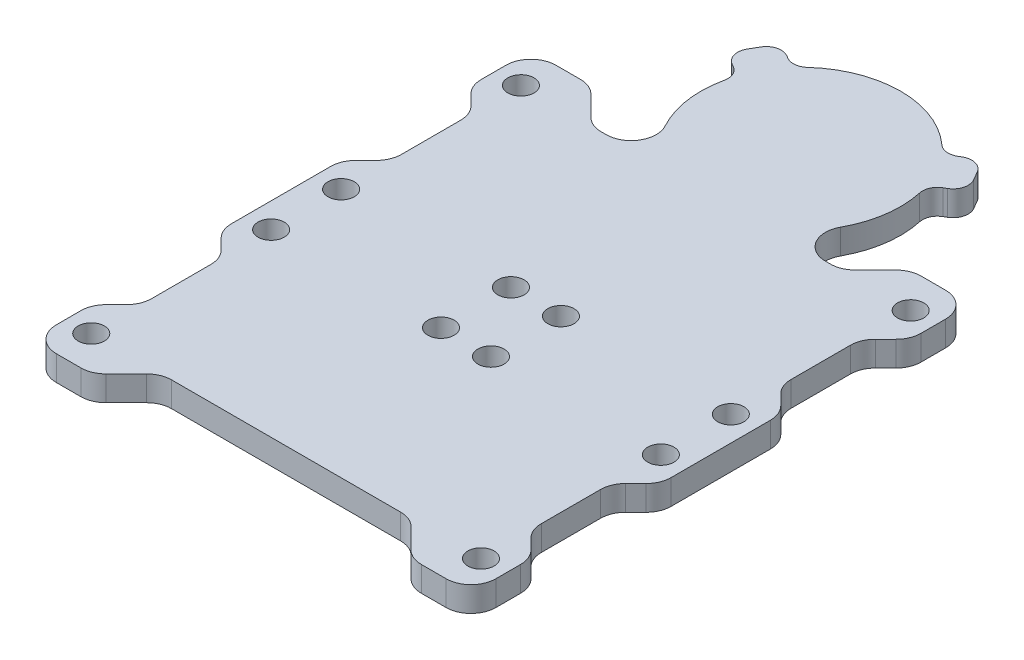
SolidWorks part; units mm, degrees
ref_plane "Front Plane" through (0, 0, 0) normal (0, 0, 1) x (1, 0, 0)
ref_plane "Top Plane" through (0, 0, 0) normal (0, 1, 0) x (1, 0, 0)
ref_plane "Right Plane" through (0, 0, 0) normal (1, 0, 0) x (0, 0, -1)
sketch "Sketch1" plane through (0, 0, 0) normal (0, 1, 0) x (1, 0, 0)
  line L0 (-42.5355, 36.5355) -> (-40.4645, 34.4645)
  line L1 (-39, 50) -> (-34.0711, 50)
  line L2 (-44, 45) -> (-44, 40.0711)
  line L3 (-39, -50) -> (-34.0711, -50)
  line L4 (44, 45) -> (44, 40.0711)
  line L5 (-39, 30.9289) -> (-39, 19.0711)
  line L6 (-40.4645, 15.5355) -> (-42.5355, 13.4645)
  line L7 (-44, 9.9289) -> (-44, -9.9289)
  line L8 (-42.5355, -13.4645) -> (-40.4645, -15.5355)
  line L9 (-39, -19.0711) -> (-39, -30.9289)
  line L10 (-40.4645, -34.4645) -> (-42.5355, -36.5355)
  line L11 (-44, -40.0711) -> (-44, -45)
  line L12 (-44, 12) -> (-44, -12)
  line L13 (-44, -40.0711) -> (-44, -50)
  line L14 (0, -55) -> (0, 55) construction
  line L15 (44, -40.0711) -> (44, -45)
  line L16 (44, 12) -> (44, -12)
  line L17 (44, -40.0711) -> (44, -45)
  line L18 (40.4645, -34.4645) -> (42.5355, -36.5355)
  line L19 (39, -19.0711) -> (39, -30.9289)
  line L20 (42.5355, -13.4645) -> (40.4645, -15.5355)
  line L21 (44, 9.9289) -> (44, -9.9289)
  line L22 (40.4645, 15.5355) -> (42.5355, 13.4645)
  line L23 (39, 30.9289) -> (39, 19.0711)
  line L24 (44, 45) -> (44, 40.0711)
  line L25 (42.5355, 36.5355) -> (40.4645, 34.4645)
  line L26 (44, -40.0711) -> (44, -45)
  line L27 (44, 12) -> (44, -12)
  line L28 (-30.5355, -48.5355) -> (-26.4645, -44.4645)
  line L29 (-22.9289, -43) -> (22.9289, -43)
  line L30 (26.4645, -44.4645) -> (30.5355, -48.5355)
  line L31 (34.0711, -50) -> (39, -50)
  line L32 (-30.5355, 48.5355) -> (-26.4645, 44.4645)
  line L33 (-22.9289, 43) -> (-21.9317, 43)
  line L34 (30.5355, 48.5355) -> (26.4645, 44.4645)
  line L35 (22.9289, 43) -> (21.9317, 43)
  line L36 (0, 60) -> (-17.3205, 70) construction
  line L37 (34.0711, 50) -> (39, 50)
  line L42 (-20.9737, 67.4903) -> (-21.5686, 67.8339)
  line L43 (-22.6667, 71.9319) -> (-21.6667, 73.664)
  line L44 (-17.5686, 74.7621) -> (-16.9737, 74.4186)
  line L45 (0, 60) -> (17.3205, 70) construction
  line L46 (17.5686, 74.7621) -> (16.9737, 74.4186)
  line L47 (22.6667, 71.9319) -> (21.6667, 73.664)
  line L48 (20.9737, 67.4903) -> (21.5686, 67.8339)
  circle A0 centre (-39, 43) radius 2.625
  circle A5 centre (-39, 7) radius 2.625
  circle A6 centre (-39, -7) radius 2.625
  circle A7 centre (-39, -43) radius 2.625
  arc A8 (-39, 50) -> (-44, 45) centre (-39, 45) ccw
  arc A9 (-42.5355, 36.5355) -> (-44, 40.0711) centre (-39, 40.0711) cw
  arc A10 (-40.4645, 34.4645) -> (-39, 30.9289) centre (-44, 30.9289) cw
  arc A11 (-39, 19.0711) -> (-40.4645, 15.5355) centre (-44, 19.0711) cw
  arc A12 (-42.5355, 13.4645) -> (-44, 9.9289) centre (-39, 9.9289) ccw
  arc A13 (-44, -9.9289) -> (-42.5355, -13.4645) centre (-39, -9.9289) ccw
  arc A14 (-40.4645, -15.5355) -> (-39, -19.0711) centre (-44, -19.0711) cw
  arc A15 (-39, -30.9289) -> (-40.4645, -34.4645) centre (-44, -30.9289) cw
  arc A16 (-42.5355, -36.5355) -> (-44, -40.0711) centre (-39, -40.0711) ccw
  arc A17 (-44, -45) -> (-39, -50) centre (-39, -45) ccw
  arc A18 (44, -45) -> (39, -50) centre (39, -45) cw
  arc A19 (42.5355, -36.5355) -> (44, -40.0711) centre (39, -40.0711) cw
  arc A20 (39, -30.9289) -> (40.4645, -34.4645) centre (44, -30.9289) ccw
  arc A21 (40.4645, -15.5355) -> (39, -19.0711) centre (44, -19.0711) ccw
  arc A22 (44, -9.9289) -> (42.5355, -13.4645) centre (39, -9.9289) cw
  arc A23 (42.5355, 13.4645) -> (44, 9.9289) centre (39, 9.9289) cw
  arc A24 (39, 19.0711) -> (40.4645, 15.5355) centre (44, 19.0711) ccw
  arc A25 (40.4645, 34.4645) -> (39, 30.9289) centre (44, 30.9289) ccw
  arc A26 (42.5355, 36.5355) -> (44, 40.0711) centre (39, 40.0711) ccw
  arc A27 (39, 50) -> (44, 45) centre (39, 45) cw
  circle A28 centre (39, -43) radius 2.625
  circle A29 centre (39, -7) radius 2.625
  circle A30 centre (39, 7) radius 2.625
  circle A31 centre (39, 43) radius 2.625
  circle A32 centre (-5, 7) radius 2.625
  circle A33 centre (5, 7) radius 2.625
  circle A34 centre (5, -7) radius 2.625
  circle A35 centre (-5, -7) radius 2.625
  arc A36 (30.5355, -48.5355) -> (34.0711, -50) centre (34.0711, -45) ccw
  arc A37 (22.9289, -43) -> (26.4645, -44.4645) centre (22.9289, -48) cw
  arc A38 (-26.4645, -44.4645) -> (-22.9289, -43) centre (-22.9289, -48) cw
  arc A39 (-30.5355, -48.5355) -> (-34.0711, -50) centre (-34.0711, -45) cw
  arc A40 (17.5454, 50.4) -> (19.5423, 64.2542) centre (0, 60) ccw
  arc A41 (30.5355, 48.5355) -> (34.0711, 50) centre (34.0711, 45) cw
  arc A42 (26.4645, 44.4645) -> (22.9289, 43) centre (22.9289, 48) cw
  arc A43 (-26.4645, 44.4645) -> (-22.9289, 43) centre (-22.9289, 48) ccw
  arc A44 (-30.5355, 48.5355) -> (-34.0711, 50) centre (-34.0711, 45) ccw
  arc A45 (-10.5707, 43) -> (-10.5654, 43.0185) centre (-10.5707, 43.01) ccw
  arc A46 (21.9317, 43) -> (17.5454, 50.4) centre (21.9317, 48) cw
  arc A47 (-17.5454, 50.4) -> (-21.9317, 43) centre (-21.9317, 48) cw
  arc A48 (-19.5423, 64.2542) -> (-17.5454, 50.4) centre (0, 60) ccw
  arc A49 (-16.9737, 74.4186) -> (-13.4554, 74.7971) centre (-15.4737, 77.0166) ccw
  arc A50 (-21.6667, 73.664) -> (-17.5686, 74.7621) centre (-19.0686, 72.164) cw
  arc A51 (-21.5686, 67.8339) -> (-22.6667, 71.9319) centre (-20.0686, 70.4319) cw
  arc A52 (-20.9737, 67.4903) -> (-19.5423, 64.2542) centre (-22.4737, 64.8923) cw
  arc A53 (16.9737, 74.4186) -> (13.4554, 74.7971) centre (15.4737, 77.0166) cw
  arc A54 (21.6667, 73.664) -> (17.5686, 74.7621) centre (19.0686, 72.164) ccw
  arc A55 (21.5686, 67.8339) -> (22.6667, 71.9319) centre (20.0686, 70.4319) ccw
  arc A56 (20.9737, 67.4903) -> (19.5423, 64.2542) centre (22.4737, 64.8923) ccw
  arc A57 (13.4554, 74.7971) -> (-13.4554, 74.7971) centre (0, 60) ccw
  point P31 (-44, 50)
  point P34 (-44, 38)
  point P98 (44, 38)
  point P101 (32, -50)
  point P108 (-32, -50)
  point P119 (32, 50)
  point P126 (-32, 50)
  point P142 (-20.1667, 76.2621)
  point P145 (-24.1667, 69.3339)
  point P148 (-18.9706, 66.3339)
  dimension "D5" = 5.25
  dimension "D6" = 5.25
  dimension "D7" = 5.25
  dimension "D8" = 5.25
  dimension "D23" = 5
  dimension "D24" = 5
  dimension "D25" = 5
  dimension "D26" = 5
  dimension "D27" = 5
  dimension "D28" = 5
  dimension "D29" = 5
  dimension "D30" = 5
  dimension "D31" = 5
  dimension "D32" = 5
  dimension "D22" = 5.25
  dimension "D33" = 5.25
  dimension "D34" = 5.25
  dimension "D35" = 5.25
  dimension "D47" = 5
  dimension "D48" = 40
  dimension "D54" = 5
  dimension "D55" = 5
  dimension "D56" = 5
  dimension "D62" = 3
  dimension "D1" = 44
  dimension "D3" = 50
  dimension "D4" = 50
  dimension "D9" = 7
  dimension "D10" = 5
  dimension "D11" = 5
  dimension "D12" = 5
  dimension "D13" = 5
  dimension "D14" = 7
  dimension "D15" = 43
  dimension "D16" = 43
  dimension "D17" = 12
  dimension "D18" = 135
  dimension "D19" = 135
  dimension "D20" = 38
  dimension "D21" = 38
  dimension "D36" = 43
  dimension "D37" = 43
  dimension "D38" = 43
  dimension "D39" = 43
  dimension "D40" = 34
  dimension "D41" = 34
  dimension "D42" = 34
  dimension "D43" = 34
  dimension "D44" = 12
  dimension "D45" = 12
  dimension "D46" = 135
  dimension "D49" = 10
  dimension "D50" = 12
  dimension "D51" = 135
  dimension "D52" = 12
  dimension "D53" = 135
  dimension "D57" = 30
  dimension "D58" = 0
  dimension "D59" = 6
  dimension "D60" = 8
  dimension "D61" = 4
extrude "Boss-Extrude1" add sketch "Sketch1" along normal blind 5
